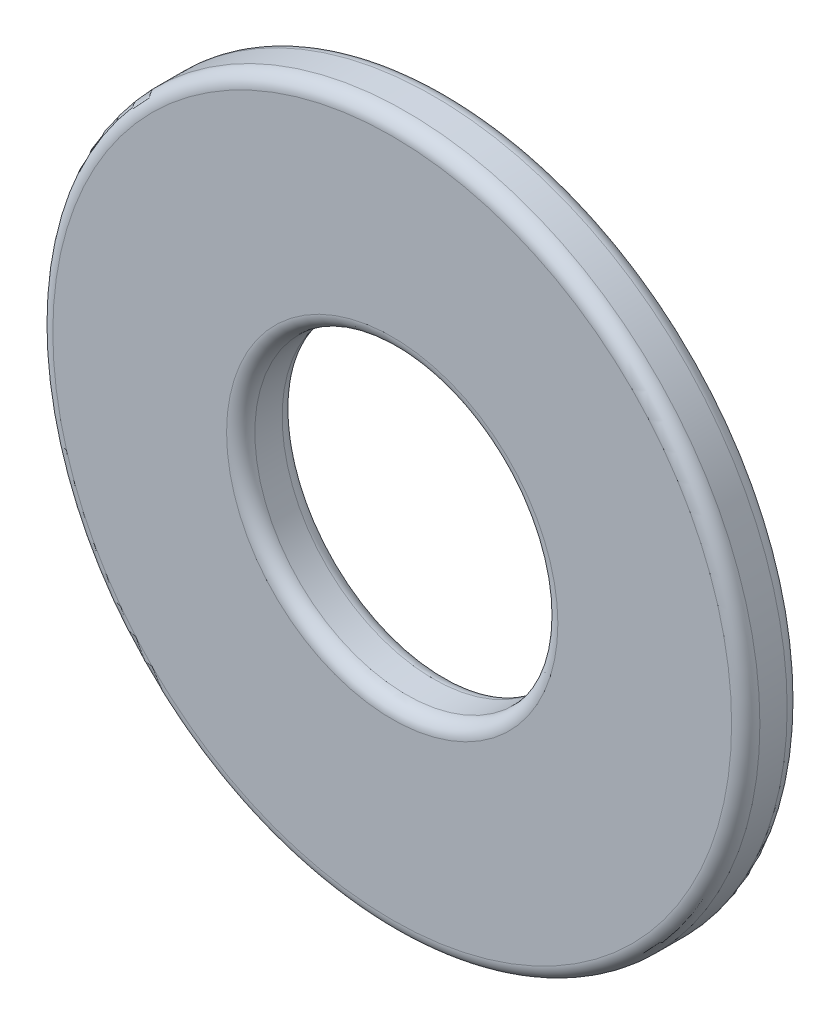
SolidWorks part; units mm, degrees
ref_plane "Front Plane" through (0, 0, 0) normal (0, 0, 1) x (1, 0, 0)
ref_plane "Top Plane" through (0, 0, 0) normal (0, 1, 0) x (1, 0, 0)
ref_plane "Right Plane" through (0, 0, 0) normal (1, 0, 0) x (0, 0, -1)
sketch "Sketch1" plane through (0, 0, 0) normal (0, 0, 1) x (1, 0, 0)
  circle A0 centre (0, 0) radius 3.5 construction
  circle A1 centre (0, 0) radius 1.5 construction
  point P5 (0, -3.5)
  dimension "OD" = 7
  dimension "ID" = 3
sketch "Sketch2" plane through (0, 0, 0) normal (1, 0, 0) x (0, 0, -1)
  line L0 (0.2, 0) -> (-0.2, 0) construction
  line L1 (-0.275, -3.5) -> (0.275, -3.5) construction
  point P0 (-0.275, -3.5)
  point P3 (0.275, -3.5)
  point P4 (0, 0)
  point P9 (0, -3.5)
  point P10 (0.2, -3.5)
  point P11 (-0.275, -3.5)
  point P12 (-0.2, -3.5)
  point P13 (0.275, -3.5)
  dimension "Thickness Range [Min]" = 0.4
  dimension "Thickness Range [Max]" = 0.55
sketch "Sketch3" plane through (0, 0, 0) normal (0, 0, 1) x (1, 0, 0)
  circle A0 centre (0, 0) radius 1.5 construction
  circle A1 centre (0, 0) radius 3.5 construction
  circle A2 centre (0, 0) radius 1.5
  circle A3 centre (0, 0) radius 3.5
extrude "Boss-Extrude1" add sketch "Sketch3" against normal up to vertex (0.275 mm away) and the other way up to vertex (0.275 mm away) up to point (0, -3.5, -0.275) other way up to point (0, -3.5, 0.275)
fillet "Fillet1" radius 0.14 4 edges at (3.5, 0, -0.275) (1.5, 0, -0.275) (1.5, 0, 0.275) (3.5, 0, 0.275)
equation "\"D1@Fillet1\"=\"OD@Sketch1\"*.02"
